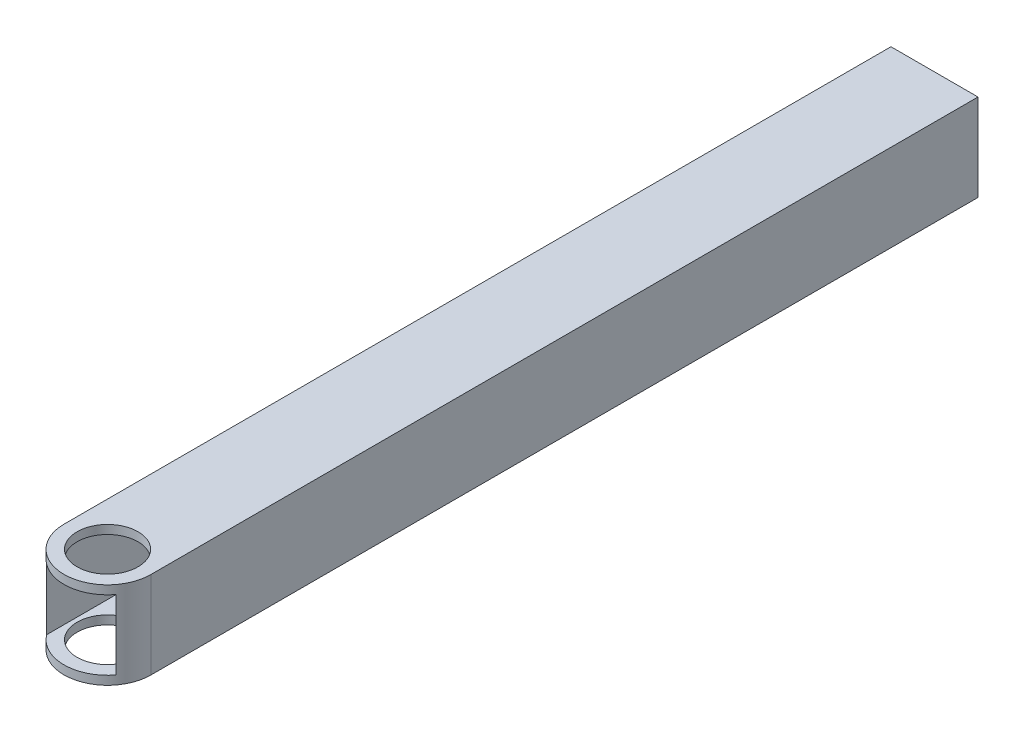
SolidWorks part; units mm, degrees
ref_plane "正面" through (0, 0, 0) normal (0, 0, 1) x (1, 0, 0)
ref_plane "平面" through (0, 0, 0) normal (0, 1, 0) x (1, 0, 0)
ref_plane "右側面" through (0, 0, 0) normal (1, 0, 0) x (0, 0, -1)
sketch "ｽｹｯﾁ1" plane through (0, 0, 0) normal (0, 0, 1) x (1, 0, 0)
  line L1 (-5, 5) -> (5, 5)
  line L2 (-5, 5) -> (-5, -5)
  line L3 (-5, -5) -> (5, -5)
  line L4 (5, 5) -> (5, -5)
  line L5 (-5, 5) -> (5, -5) construction
  line L6 (-5, -5) -> (5, 5) construction
  line L7 (-4, 4) -> (4, 4)
  line L8 (-4, 4) -> (-4, -4)
  line L9 (-4, -4) -> (4, -4)
  line L10 (4, 4) -> (4, -4)
  line L11 (-4, 4) -> (4, -4) construction
  line L12 (-4, -4) -> (4, 4) construction
  point P0 (0, 0)
  point P6 (0, 0)
  dimension "D1" = 10
  dimension "D2" = 8
extrude "ﾎﾞｽ - 押し出し1" add sketch "ｽｹｯﾁ1" along normal blind 100
sketch "ｽｹｯﾁ2" plane through (0, 5, 0) normal (0, 1, 0) x (1, 0, 0)
  line L0 (-5, -100) -> (-5, 0) construction
  line L1 (5, -100) -> (-5, -100) construction
  line L2 (5, -100) -> (5, 0) construction
  line L3 (-5, -95) -> (-5, -103)
  line L4 (-5, -103) -> (5, -103)
  line L5 (5, -103) -> (5, -95)
  arc A0 (-5, -95) -> (5, -95) centre (0, -95) ccw
  circle A1 centre (0, -95) radius 3.5
  dimension "D1" = 7
  dimension "D2" = 8
extrude "ｶｯﾄ - 押し出し1" cut sketch "ｽｹｯﾁ2" against normal blind 100
